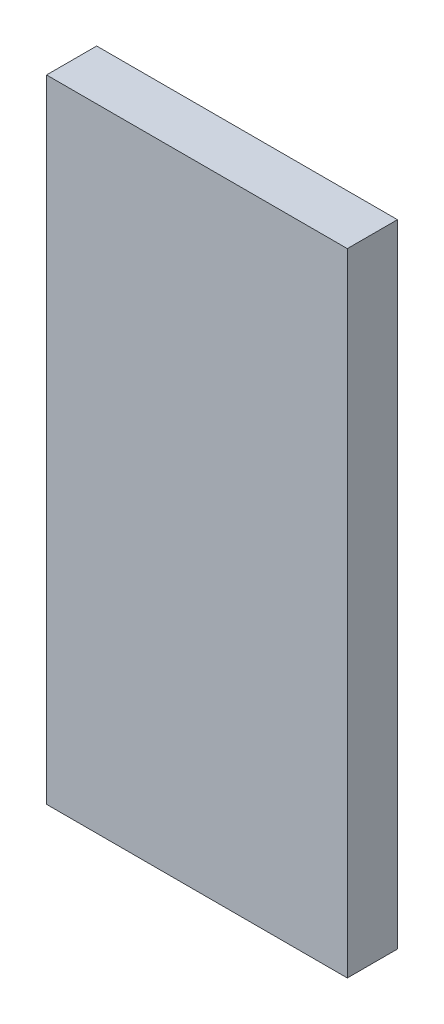
SolidWorks part; units mm, degrees
ref_plane "Front Plane" through (0, 0, 0) normal (0, 0, 1) x (1, 0, 0)
ref_plane "Top Plane" through (0, 0, 0) normal (0, 1, 0) x (1, 0, 0)
ref_plane "Right Plane" through (0, 0, 0) normal (1, 0, 0) x (0, 0, -1)
sketch "Sketch1" plane through (0, 0, 0) normal (0, 0, 1) x (1, 0, 0)
  line L1 (-28.0306, 40.7071) -> (1.9694, 40.7071)
  line L2 (-28.0306, 40.7071) -> (-28.0306, -22.2929)
  line L3 (-28.0306, -22.2929) -> (1.9694, -22.2929)
  line L4 (1.9694, 40.7071) -> (1.9694, -22.2929)
  dimension "D1" = 30
  dimension "D2" = 63
  dimension "D3" = 1.9694
  dimension "D4" = 40.7071
extrude "Boss-Extrude1" add sketch "Sketch1" along normal blind 5
